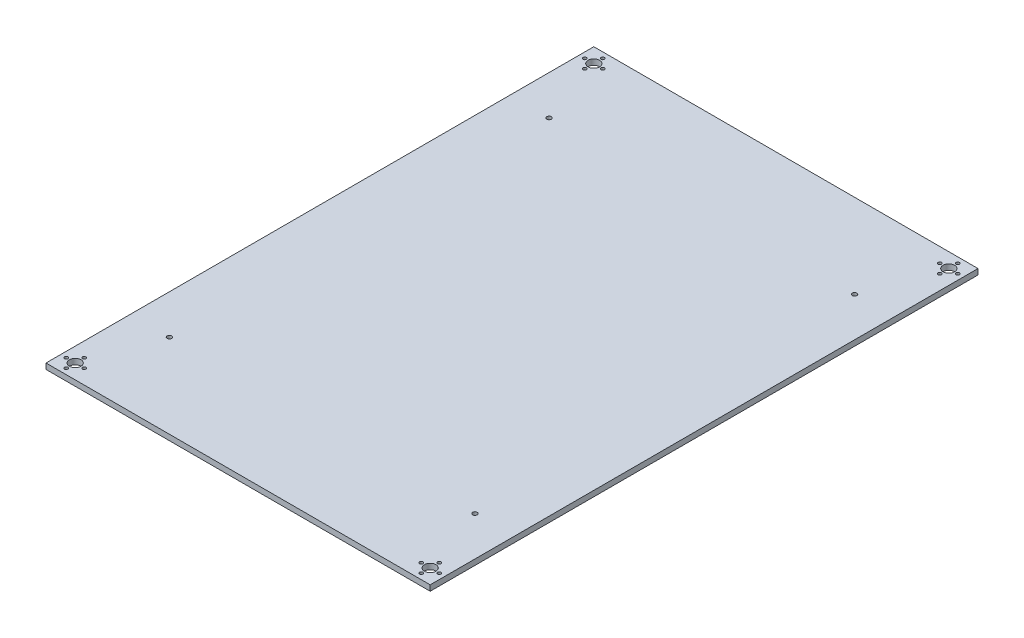
SolidWorks part; units mm, degrees
ref_plane "Front Plane" through (0, 0, 0) normal (0, 0, 1) x (1, 0, 0)
ref_plane "Top Plane" through (0, 0, 0) normal (0, 1, 0) x (1, 0, 0)
ref_plane "Right Plane" through (0, 0, 0) normal (1, 0, 0) x (0, 0, -1)
sketch "Sketch1" plane through (0, 0, 0) normal (1, 0, 0) x (0, 0, -1)
  line L0 (0, 0) -> (-487.65, 0)
  line L1 (-487.65, 0) -> (-487.65, 5)
  line L2 (-487.65, 5) -> (0, 5)
  line L6 (0, 5) -> (0, 0)
  dimension "D1" = 487.65
  dimension "D2" = 5
extrude "Boss-Extrude1" add sketch "Sketch1" along normal blind 342
sketch "ThreadedRod'Holes-Sketch2" plane through (0, 5, 0) normal (0, 1, 0) x (1, 0, 0)
  line L0 (342, 0) -> (0, 0) construction
  line L1 (342, 0) -> (342, -487.65) construction
  line L3 (342, -487.65) -> (0, -487.65) construction
  line L4 (0, 0) -> (0, -487.65) construction
  circle A0 centre (329, -13) radius 5.1
  circle A2 centre (321, -13) radius 1.5
  circle A3 centre (329, -5) radius 1.5
  circle A6 centre (329, -21) radius 1.5
  circle A7 centre (337, -13) radius 1.5
  circle A10 centre (21, -13) radius 1.5
  circle A11 centre (13, -21) radius 1.5
  circle A12 centre (13, -5) radius 1.5
  circle A13 centre (5, -13) radius 1.5
  circle A14 centre (13, -13) radius 5.1
  circle A16 centre (13, -482.65) radius 1.5
  circle A17 centre (21, -474.65) radius 1.5
  circle A18 centre (5, -474.65) radius 1.5
  circle A19 centre (13, -466.65) radius 1.5
  circle A20 centre (321, -474.65) radius 1.5
  circle A21 centre (329, -482.65) radius 1.5
  circle A22 centre (329, -466.65) radius 1.5
  circle A23 centre (337, -474.65) radius 1.5
  circle A25 centre (13, -474.65) radius 5.1
  circle A26 centre (329, -474.65) radius 5.1
  dimension "D9" = 3
  dimension "D10" = 10.2
  dimension "D17" = 316
  dimension "D3" = 8
  dimension "D4" = 8
  dimension "D5" = 8
  dimension "D6" = 8
  dimension "D7" = 8
  dimension "D8" = 8
  dimension "D11" = 8
  dimension "D12" = 8
  dimension "D13" = 13
  dimension "D14" = 13
  dimension "D2" = 461.65
  dimension "D15" = 13
  dimension "D16" = 13
  dimension "D18" = 342
  dimension "D19" = 487.65
  dimension "D20" = 342
  dimension "D21" = 474.65
  dimension "D22" = 329
extrude "ThreadedRodHoles-Cut-Extrude1" cut sketch "ThreadedRod'Holes-Sketch2" against normal through all
sketch "BaseOlateMountHolesSketch2" plane through (0, 5, 0) normal (0, 1, 0) x (1, 0, 0)
  line L0 (342, -487.65) -> (0, -487.65) construction
  line L1 (342, 0) -> (0, 0) construction
  line L2 (342, -487.65) -> (342, 0) construction
  line L3 (0, 0) -> (0, -487.65) construction
  line L4 (0, -487.65) -> (0, 0) construction
  line L5 (342, 0) -> (342, -487.65) construction
  circle A0 centre (35, -74.825) radius 2
  circle A1 centre (307, -74.825) radius 2
  circle A2 centre (307, -412.825) radius 2
  circle A3 centre (35, -412.825) radius 2
  dimension "D5" = 4
  dimension "D1" = 74.825
  dimension "D2" = 74.825
  dimension "D3" = 35
  dimension "D4" = 35
  dimension "D6" = 338
  dimension "D7" = 272
  dimension "D8" = 487.65
  dimension "D9" = 342
  dimension "D10" = 412.825
  dimension "D11" = 307
extrude "BasePlateMountHolesCut-Extrude1" cut sketch "BaseOlateMountHolesSketch2" against normal through all
equation "\"RailThickness\"= .125in'Spec"
equation "\"StepperMountingHoleDistance\"= 31mm'Spec"
equation "\"StepperMountingHoleOffsetFromLeftOrRightSide\"= \"StepperMountingHoleOffsetFromItsSide\" + \"RailThickness\"'Spec"
equation "\"StepperMountingHoleOffsetFromItsSide\"= 5.5mm'Spec"
equation "\"LeadScrewNutMountingHoleDiameter\"=3"
equation "\"D9@ThreadedRod'Holes-Sketch2\" = \"LeadScrewNutMountingHoleDiameter\""
equation "\"D10@ThreadedRod'Holes-Sketch2\" = \"LeadScrewNutInnerShaftFlangeDiameter\""
equation "\"D1@Boss-Extrude1\" = \"BasePlateLength\""
equation "\"BedThirdSize\"= 70mm"
equation "\"BedInnerSquareWidth\"= \"BedThirdSize\" * 3'Equals 210"
equation "\"BedInnerSquareLength\"= \"BedInnerSquareWidth\""
equation "\"BedLWidth\"= \"BedThirdSize\"'Equals 70"
equation "\"BedLength\"= \"BedInnerSquareLength\" + \"BedLWidth\" * 2 + \"BedIncreasedByLength\"'Equals 350"
equation "\"DistanceBetweenFrontToBackStepperHoles\"= \"BedLength\" - \"DistanceFromBedFrontToFirstLeftStepperHole\"'Equals 316"
equation "\"DistanceFromBedFrontToFirstLeftStepperHole\"= \"LeadScrewNutPadSize\" + 10mm'Equals 34"
equation "\"BedIncreasedByLength\"= 0mm"
equation "\"D17@ThreadedRod'Holes-Sketch2\" = \"DistanceBetweenFrontToBackStepperHoles\""
equation "\"LeadScrewNutMountingHoleFlangeDiameter\"= 22mm'Spec"
equation "\"LeadScrewNutPadSize\"= \"LeadScrewNutMountingHoleFlangeDiameter\" + 2mm'Equals 24"
equation "\"BaseThickness\"= 5mm"
equation "\"FrontBackRailLength\"= 510mm"
equation "\"D1@Sketch1\"= \"BasePlateWidth\""
equation "\"D2@Sketch1\"=\"BaseThickness\""
equation "\"LeadScrewNutInnerShaftFlangeDiameter\"= 10.2mm'Spec"
equation "\"LeadScrewNutMountingHoleDistance\"= 16mm"
equation "\"D3@ThreadedRod'Holes-Sketch2\" = \"LeadScrewNutMountingHoleDistance\" / 2"
equation "\"D4@ThreadedRod'Holes-Sketch2\" = \"LeadScrewNutMountingHoleDistance\" / 2"
equation "\"D5@ThreadedRod'Holes-Sketch2\" = \"LeadScrewNutMountingHoleDistance\" / 2"
equation "\"D6@ThreadedRod'Holes-Sketch2\" = \"LeadScrewNutMountingHoleDistance\" / 2"
equation "\"D7@ThreadedRod'Holes-Sketch2\" = \"LeadScrewNutMountingHoleDistance\" / 2"
equation "\"D8@ThreadedRod'Holes-Sketch2\" = \"LeadScrewNutMountingHoleDistance\" / 2"
equation "\"D11@ThreadedRod'Holes-Sketch2\" = \"LeadScrewNutMountingHoleDistance\" / 2"
equation "\"D12@ThreadedRod'Holes-Sketch2\" = \"LeadScrewNutMountingHoleDistance\" / 2"
equation "\"D13@ThreadedRod'Holes-Sketch2\" = \"LeadScrewNutPadSize\" / 2 + 1mm"
equation "\"D14@ThreadedRod'Holes-Sketch2\" = \"LeadScrewNutPadSize\" / 2 + 1mm"
equation "\"DistanceBetweenLeftToRightStepperHoles\"= \"FrontBackRailLength\" - \"StepperMountingHoleOffsetFromLeftOrRightSide\" * 2 - \"StepperMountingHoleDistance\"'Equals 461.65"
equation "\"BasePlateWidth\"= \"DistanceBetweenLeftToRightStepperHoles\" + \"LeadScrewNutPadSize\" + 2mm"
equation "\"BasePlateLength\"= \"DistanceBetweenFrontToBackStepperHoles\" + \"LeadScrewNutPadSize\" + 2mm"
equation "\"D2@ThreadedRod'Holes-Sketch2\" = \"DistanceBetweenLeftToRightStepperHoles\""
equation "\"BuildPlateWidth\"= 352mm"
equation "\"BuildPlateLength\"= 352mm"
equation "\"BuildPlateStandoffHoleDistanceFromLeftOrRight\"= 7mm"
equation "\"BuildPlateStandoffHoleDistanceFromFrontOrBack\"= 40mm"
equation "\"D1@BaseOlateMountHolesSketch2\"=( \"BasePlateWidth\" - \"BuildPlateWidth\" + \"BuildPlateStandoffHoleDistanceFromLeftOrRight\" * 2)  / 2"
equation "\"D2@BaseOlateMountHolesSketch2\"=( \"BasePlateWidth\" - \"BuildPlateWidth\"  + \"BuildPlateStandoffHoleDistanceFromLeftOrRight\" * 2)  / 2"
equation "\"D3@BaseOlateMountHolesSketch2\"=(\"BasePlateLength\" - (\"BuildPlateLength\" - \"BuildPlateStandoffHoleDistanceFromFrontOrBack\"*2))/2"
equation "\"D4@BaseOlateMountHolesSketch2\"=(\"BasePlateLength\" -(\"BuildPlateLength\" -\"BuildPlateStandoffHoleDistanceFromFrontOrBack\"*2))/2"
